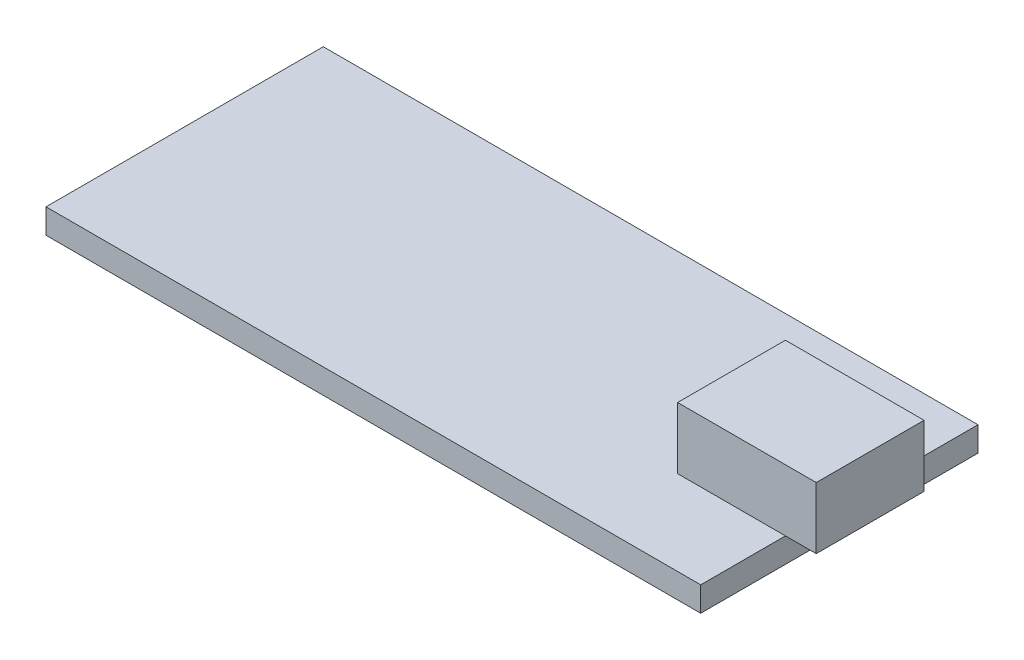
SolidWorks part; units mm, degrees
ref_plane "Plano frontal" through (0, 0, 0) normal (0, 0, 1) x (1, 0, 0)
ref_plane "Plano superior" through (0, 0, 0) normal (0, 1, 0) x (1, 0, 0)
ref_plane "Plano direito" through (0, 0, 0) normal (1, 0, 0) x (0, 0, -1)
sketch "Esboço1" plane through (0, 0, 0) normal (0, 1, 0) x (1, 0, 0)
  line L1 (-21.25, -9) -> (21.25, -9)
  line L2 (-21.25, -9) -> (-21.25, 9)
  line L3 (-21.25, 9) -> (21.25, 9)
  line L4 (21.25, -9) -> (21.25, 9)
  line L5 (-21.25, -9) -> (21.25, 9) construction
  line L6 (-21.25, 9) -> (21.25, -9) construction
  point P0 (0, 0)
  dimension "D1" = 42.5
  dimension "D2" = 18
extrude "Ressalto-extrusão1" add sketch "Esboço1" against normal blind 1.6
sketch "Esboço2" plane through (0, 0, 0) normal (0, 1, 0) x (1, 0, 0)
  line L0 (0, 0) -> (21.25, 0) construction
  line L1 (21.25, -9) -> (21.25, 9) construction
  line L2 (21.25, 3.5) -> (23.25, 3.5)
  line L3 (21.25, 3.5) -> (14.25, 3.5)
  line L4 (14.25, 3.5) -> (14.25, -3.5)
  line L5 (23.25, 3.5) -> (23.25, -3.5)
  line L6 (21.25, -3.5) -> (23.25, -3.5)
  line L7 (21.25, -3.5) -> (14.25, -3.5)
  point P11 (23.25, 0)
  point P13 (14.25, 0)
  dimension "D1" = 2
  dimension "D2" = 7
  dimension "D3" = 3.5
extrude "Ressalto-extrusão2" add sketch "Esboço2" along normal blind 4
